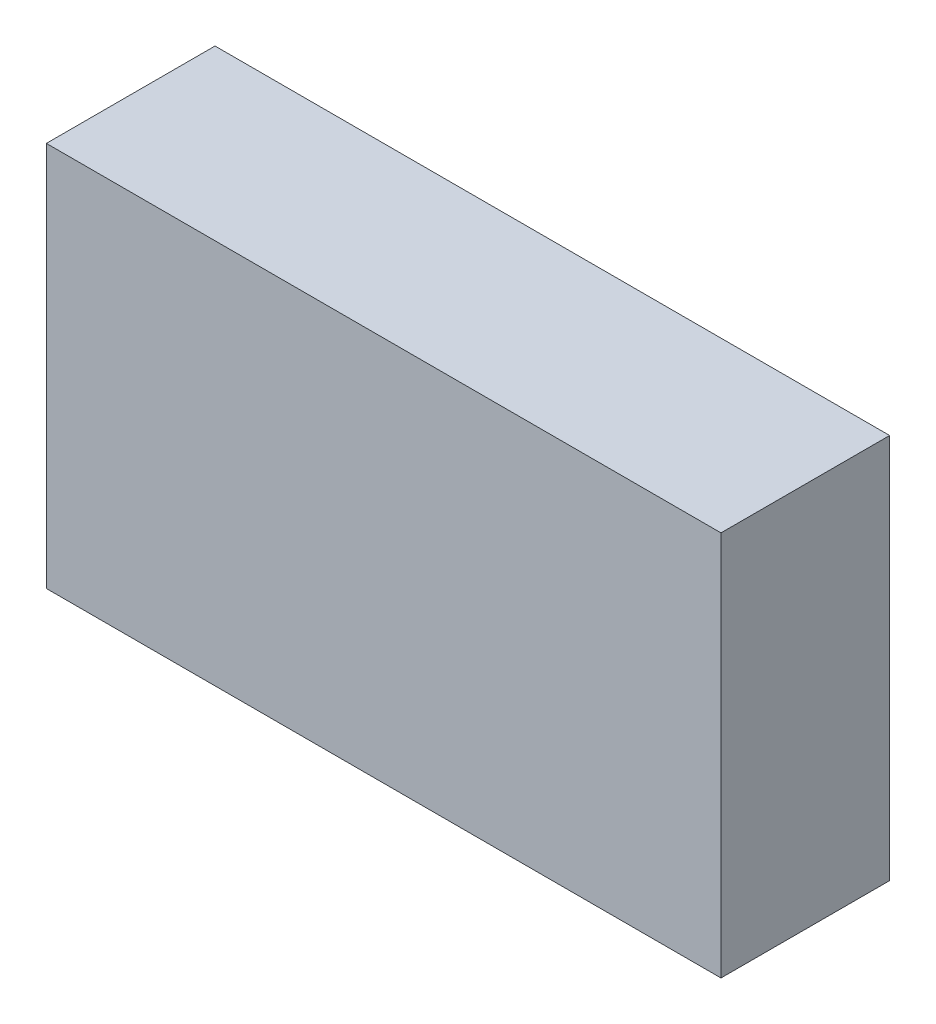
SolidWorks part; units mm, degrees
ref_plane "Front Plane" through (0, 0, 0) normal (0, 0, 1) x (1, 0, 0)
ref_plane "Top Plane" through (0, 0, 0) normal (0, 1, 0) x (1, 0, 0)
ref_plane "Right Plane" through (0, 0, 0) normal (1, 0, 0) x (0, 0, -1)
sketch "Sketch2" plane through (0, 0, 0) normal (0, 1, 0) x (1, 0, 0)
  line L0 (-88.9, 0) -> (88.9, 0)
  line L1 (88.9, 0) -> (88.9, -44.45)
  line L2 (88.9, -44.45) -> (-88.9, -44.45)
  line L3 (-88.9, -44.45) -> (-88.9, 0)
  point P4 (0, 0)
  dimension "D1" = 177.8
  dimension "D2" = 44.45
extrude "Boss-Extrude1" add sketch "Sketch2" against normal blind 101.6
